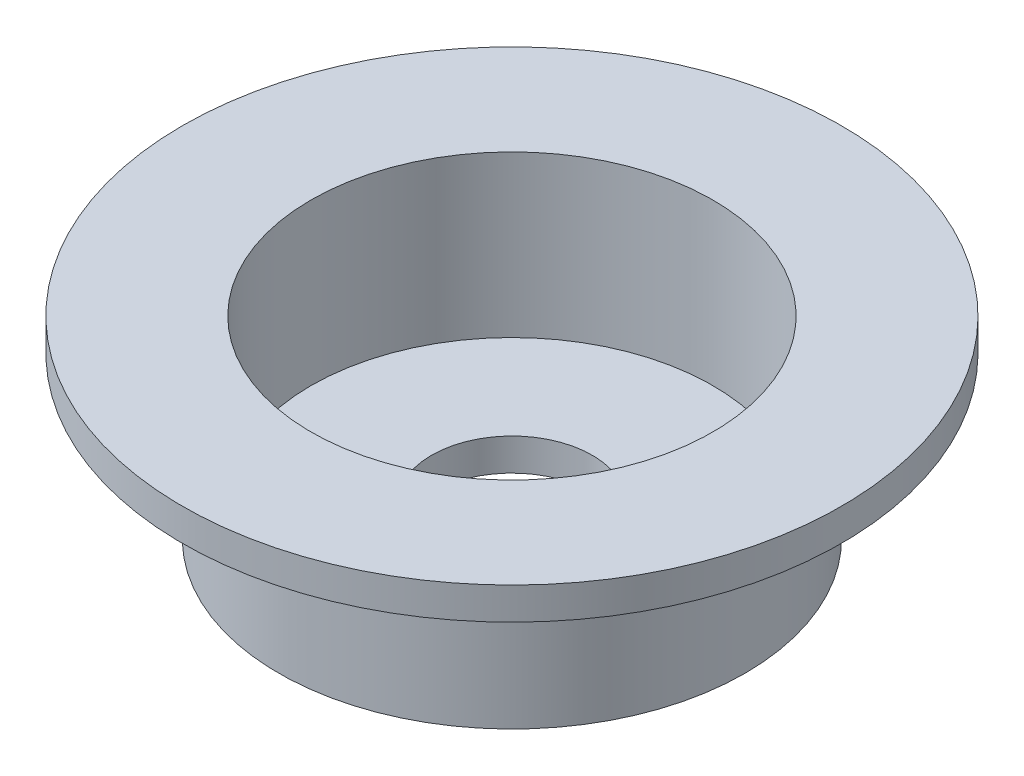
SolidWorks part; units mm, degrees
ref_plane "Front Plane" through (0, 0, 0) normal (0, 0, 1) x (1, 0, 0)
ref_plane "Top Plane" through (0, 0, 0) normal (0, 1, 0) x (1, 0, 0)
ref_plane "Right Plane" through (0, 0, 0) normal (1, 0, 0) x (0, 0, -1)
sketch "Sketch1" plane through (0, 0, 0) normal (0, 0, 1) x (1, 0, 0)
  line L0 (0, 0) -> (-8, 0)
  line L1 (-8, 0) -> (-8, -2)
  line L2 (-8, -2) -> (-2, -3)
  line L3 (-2, -3) -> (-2, -12)
  line L4 (-2, -12) -> (7.5, -12)
  line L5 (7.5, -12) -> (7.5, -10)
  line L6 (7.5, -10) -> (0, -10)
  line L7 (0, -10) -> (0, 0)
  line L8 (12.5, 0) -> (12.5, -12) construction
  dimension "D1" = 9.5
  dimension "D2" = 1
  dimension "D3" = 10
  dimension "D4" = 7.5
  dimension "D5" = 8
  dimension "D6" = 2
  dimension "D7" = 2
  dimension "D8" = 9
  dimension "D9" = 12.5
  dimension "D10" = 5
revolve "Revolve1" add sketch "Sketch1" angle 360 about L8
